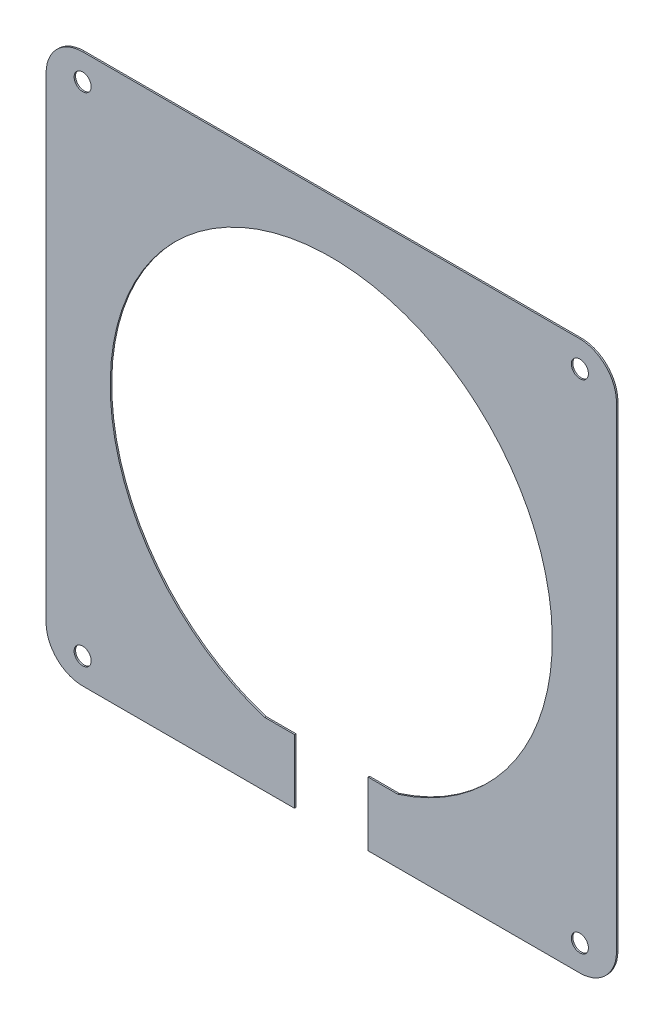
SolidWorks part; units mm, degrees
ref_plane "Front Plane" through (0, 0, 0) normal (0, 0, 1) x (1, 0, 0)
ref_plane "Top Plane" through (0, 0, 0) normal (0, 1, 0) x (1, 0, 0)
ref_plane "Right Plane" through (0, 0, 0) normal (1, 0, 0) x (0, 0, -1)
sketch "Sketch2" plane through (0, 0, 0) normal (0, 0, 1) x (1, 0, 0)
  line L0 (-11.5, -36.4562) -> (11.5, -36.4562)
  line L1 (0, 38.227) -> (0, -36.4562) construction
  line L3 (-49.325, 47.5) -> (49.325, 47.5)
  line L4 (-49.325, 47.5) -> (-49.325, -47.5)
  line L5 (-49.325, -47.5) -> (49.325, -47.5)
  line L6 (49.325, 47.5) -> (49.325, -47.5)
  line L7 (-49.325, 47.5) -> (49.325, -47.5) construction
  line L8 (-49.325, -47.5) -> (49.325, 47.5) construction
  line L9 (-43, 43) -> (43, 43) construction
  line L10 (-43, 43) -> (-43, -43) construction
  line L11 (-43, -43) -> (43, -43) construction
  line L12 (-6.35, -36.4562) -> (-6.35, -47.5)
  line L13 (6.35, -36.4562) -> (6.35, -47.5)
  line L14 (43, 43) -> (43, -43) construction
  line L15 (0, -43) -> (0, 43) construction
  line L16 (-43, 0) -> (43, 0) construction
  circle A0 centre (0, 0) radius 38.227
  circle A1 centre (-43, 43) radius 1.475
  circle A2 centre (43, 43) radius 1.475
  circle A3 centre (43, -43) radius 1.475
  circle A4 centre (-43, -43) radius 1.475
  dimension "D1" = 76.454
  dimension "D4" = 2.95
  dimension "D3" = 98.65
  dimension "D8" = 12.7
  dimension "D9" = 6.35
  dimension "D10" = 95
  dimension "D2" = 23
  dimension "D5" = 86
extrude "Boss-Extrude1" add sketch "Sketch2" along normal blind 0.254
fillet "Fillet1" radius 6.35 4 edges at (-49.325, -47.5, 0.127) (49.325, -47.5, 0.127) (49.325, 47.5, 0.127) (-49.325, 47.5, 0.127)
equation "\"D9@Sketch2\"=\"D8@Sketch2\"/2"
equation "\"D10@Sketch2\"=97.500mm-1.25*2"
